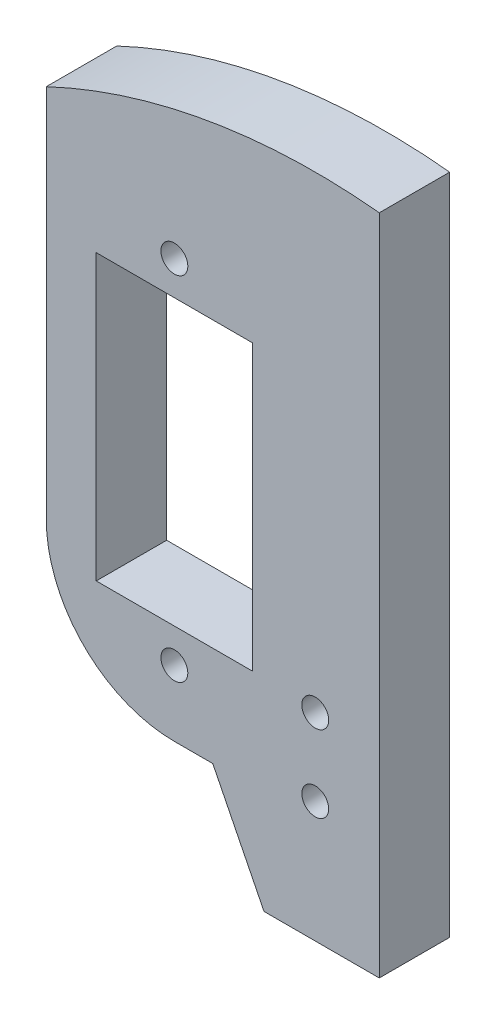
SolidWorks part; units mm, degrees
material "ﾁｰｸ材"
ref_plane "正面" through (0, 0, 0) normal (0, 0, 1) x (1, 0, 0)
ref_plane "平面" through (0, 0, 0) normal (0, 1, 0) x (1, 0, 0)
ref_plane "右側面" through (0, 0, 0) normal (1, 0, 0) x (0, 0, -1)
sketch "ｽｹｯﾁ1" plane through (0, 0, 0) normal (0, 0, 1) x (1, 0, 0)
  line L0 (-10, -18.9) -> (3, -18.9)
  line L1 (16, 26.1) -> (-10, 26.1)
  line L2 (16, 26.1) -> (16, -26.9)
  line L4 (-10, 26.1) -> (-10, -18.9)
  line L5 (3, -18.9) -> (7, -26.9)
  line L6 (7, -26.9) -> (16, -26.9)
  line L7 (6.1, 11.1) -> (-6.1, 11.1)
  line L8 (6.1, 11.1) -> (6.1, -11.1)
  line L9 (6.1, -11.1) -> (-6.1, -11.1)
  line L10 (-6.1, 11.1) -> (-6.1, -11.1)
  line L11 (6.1, 11.1) -> (-6.1, -11.1) construction
  line L12 (6.1, -11.1) -> (-6.1, 11.1) construction
  circle A0 centre (0, -13.75) radius 1.05
  circle A1 centre (0, 13.75) radius 1.05
  circle A2 centre (11, -17.45) radius 1.05
  circle A3 centre (11, -11.45) radius 1.05
  circle A4 centre (11, -23.9) radius 1.5 construction
  point P0 (0, 0)
  point P5 (0, 0)
  point P23 (16, -18.9152)
  point P25 (0, 0)
  point P26 (16, -25.0325)
  dimension "D3" = 2.1
  dimension "D10" = 2.1
  dimension "D12" = 3
  dimension "D1" = 22.2
  dimension "D2" = 12.2
  dimension "D4" = 2.65
  dimension "D5" = 2.65
  dimension "D6" = 18.9
  dimension "D7" = 10
  dimension "D8" = 16
  dimension "D9" = 3
  dimension "D11" = 6
  dimension "D13" = 12.45
  dimension "D14" = 5
  dimension "D15" = 26.1
  dimension "D16" = 9
  dimension "D17" = 13
  dimension "D18" = 26.9
extrude "ﾎﾞｽ - 押し出し1" add sketch "ｽｹｯﾁ1" along normal blind 5.5
sketch "ｽｹｯﾁ2" plane through (0, 0, 5.5) normal (0, 0, 1) x (1, 0, 0)
  line L0 (-10, 26.1) -> (-10, -18.9) construction
  line L1 (16, 26.1) -> (16, -26.9) construction
  line L2 (-10, 20.3719) -> (-10, 26.1)
  line L3 (-10, 26.1) -> (16, 26.1)
  line L4 (16, 26.1) -> (16, 24.8442)
  arc A0 (-10, 20.3719) -> (16, 24.8442) centre (11, -23.9) cw
  dimension "D1" = 49
extrude "ｶｯﾄ - 押し出し1" cut sketch "ｽｹｯﾁ2" against normal through all
fillet "ﾌｨﾚｯﾄ1" radius 10 1 edges at (-10, -18.9, 2.75)
